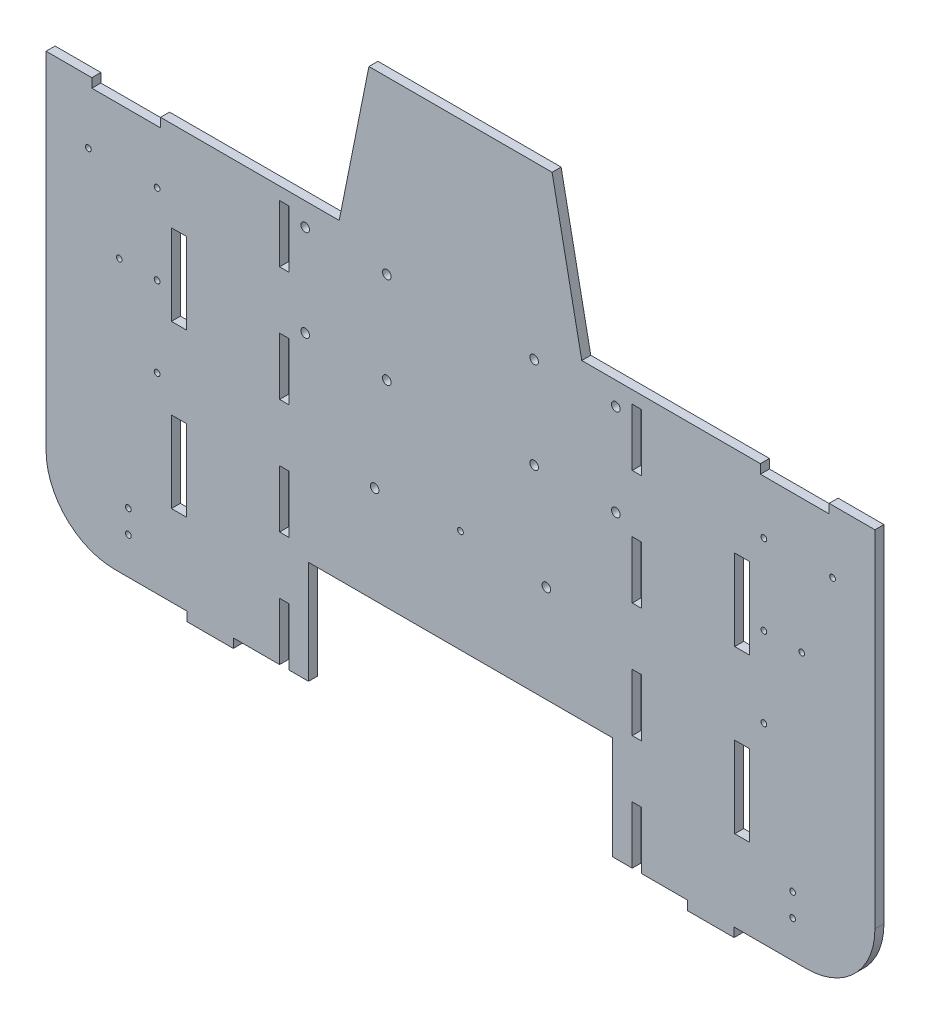
SolidWorks part; units mm, degrees
ref_plane "Front Plane" through (0, 0, 0) normal (0, 0, 1) x (1, 0, 0)
ref_plane "Top Plane" through (0, 0, 0) normal (0, 1, 0) x (1, 0, 0)
ref_plane "Right Plane" through (0, 0, 0) normal (1, 0, 0) x (0, 0, -1)
sketch "Sketch2" plane through (0, 0, 0) normal (0, 0, 1) x (1, 0, 0)
  line L0 (-408.9218, 152.7574) -> (-459.7218, 152.7574)
  line L1 (332.7218, 152.7574) -> (134.539, 152.7574)
  line L2 (-134.539, 152.7574) -> (-332.7218, 152.7574)
  line L3 (-101.6, 317.1426) -> (-134.539, 152.7574)
  line L4 (101.6, 317.1426) -> (-101.6, 317.1426)
  line L5 (-303.5218, -317.1426) -> (-303.5218, -306.9826)
  line L6 (-459.7218, 152.7574) -> (-459.7218, -230.7826)
  line L7 (459.7218, 152.7574) -> (408.9218, 152.7574)
  line L8 (-303.5218, -306.9826) -> (-383.5218, -306.9826)
  line L9 (-303.5218, -317.1426) -> (-252, -317.1426)
  line L10 (-168.529, -306.9826) -> (-190.5, -306.9826)
  line L11 (408.9218, 142.5974) -> (408.9218, 152.7574)
  line L12 (332.7218, 142.5974) -> (408.9218, 142.5974)
  line L13 (332.7218, 152.7574) -> (332.7218, 142.5974)
  line L14 (-408.9218, 142.5974) -> (-332.7218, 142.5974)
  line L15 (-408.9218, 152.7574) -> (-408.9218, 142.5974)
  line L16 (-332.7218, 142.5974) -> (-332.7218, 152.7574)
  line L17 (304.1585, -37.2346) -> (320.675, -37.2346)
  line L18 (304.1585, 52.6814) -> (304.1585, -37.2346)
  line L19 (320.675, 52.6814) -> (304.1585, 52.6814)
  line L20 (320.675, -37.2346) -> (320.675, 52.6814)
  line L21 (304.1585, -217.0666) -> (320.675, -217.0666)
  line L22 (320.675, -217.0666) -> (320.675, -127.1506)
  line L23 (320.675, -127.1506) -> (304.1585, -127.1506)
  line L24 (304.1585, -127.1506) -> (304.1585, -217.0666)
  line L25 (252, -306.9826) -> (200.66, -306.9826)
  line L26 (252, -317.1426) -> (252, -306.9826)
  line L27 (0, 317.1426) -> (0, 0) construction
  line L28 (0, 0) -> (0, -192.6826) construction
  line L30 (-320.675, -217.0666) -> (-304.1585, -217.0666)
  line L31 (-320.675, -127.1506) -> (-320.675, -217.0666)
  line L32 (-304.1585, -127.1506) -> (-320.675, -127.1506)
  line L33 (-304.1585, -217.0666) -> (-304.1585, -127.1506)
  line L34 (-304.1585, 52.6814) -> (-320.675, 52.6814)
  line L35 (-320.675, 52.6814) -> (-320.675, -37.2346)
  line L36 (-320.675, -37.2346) -> (-304.1585, -37.2346)
  line L37 (-304.1585, -37.2346) -> (-304.1585, 52.6814)
  line L38 (303.5218, -317.1426) -> (303.5218, -306.9826)
  line L39 (303.5218, -306.9826) -> (383.5218, -306.9826)
  line L40 (-252, -317.1426) -> (-252, -306.9826)
  line L41 (168.529, -306.9826) -> (168.529, -192.6826)
  line L42 (168.529, -192.6826) -> (-168.529, -192.6826)
  line L43 (-168.529, -192.6826) -> (-168.529, -306.9826)
  line L44 (-190.5, 75.1277) -> (-190.5, 11.4601) construction
  line L45 (-190.5, -52.225) -> (-190.5, -115.91) construction
  line L46 (-190.5, -179.5951) -> (-190.5, -243.2802) construction
  line L47 (190.5, 75.1277) -> (190.5, 14.3511) construction
  line L48 (190.5, -306.9826) -> (190.5, -243.2802)
  line L49 (190.5, 14.3511) -> (190.5, -115.91) construction
  line L50 (-190.5, -243.2802) -> (-190.5, -306.9826)
  line L51 (-200.66, -306.9826) -> (-252, -306.9826)
  line L52 (190.5, -115.91) -> (190.5, -243.2802) construction
  line L54 (190.5, -306.9826) -> (168.529, -306.9826)
  line L56 (459.7218, 152.7574) -> (459.7218, -230.7826)
  line L62 (101.6, 317.1426) -> (134.539, 152.7574)
  line L75 (200.66, -243.2802) -> (190.5, -243.2802)
  line L76 (200.66, -243.2802) -> (200.66, -306.9826)
  line L77 (-200.66, -243.2802) -> (-200.66, -306.9826)
  line L78 (-200.66, -243.2802) -> (-190.5, -243.2802)
  line L79 (200.66, -179.5951) -> (190.5, -179.5951)
  line L80 (190.5, -179.5951) -> (190.5, -115.91)
  line L81 (200.66, -115.91) -> (190.5, -115.91)
  line L82 (200.66, -115.91) -> (200.66, -179.5951)
  line L83 (190.5, -52.225) -> (190.5, 11.4601)
  line L84 (200.66, 11.4601) -> (190.5, 11.4601)
  line L85 (200.66, 11.4601) -> (200.66, -52.225)
  line L86 (200.66, -52.225) -> (190.5, -52.225)
  line L87 (200.66, 138.8128) -> (190.5, 138.8128)
  line L88 (190.5, 75.1277) -> (190.5, 138.8128)
  line L89 (200.66, 75.1277) -> (190.5, 75.1277)
  line L90 (200.66, 138.8128) -> (200.66, 75.1277)
  line L91 (-190.5, 75.1277) -> (-190.5, 138.8128)
  line L92 (-200.66, 138.8128) -> (-190.5, 138.8128)
  line L93 (-200.66, 138.8128) -> (-200.66, 75.1277)
  line L94 (-200.66, 75.1277) -> (-190.5, 75.1277)
  line L95 (-190.5, -52.225) -> (-190.5, 11.4601)
  line L96 (-200.66, 11.4601) -> (-190.5, 11.4601)
  line L97 (-200.66, 11.4601) -> (-200.66, -52.225)
  line L98 (-200.66, -52.225) -> (-190.5, -52.225)
  line L99 (-200.66, -115.91) -> (-200.66, -179.5951)
  line L100 (-200.66, -115.91) -> (-190.5, -115.91)
  line L101 (-190.5, -179.5951) -> (-190.5, -115.91)
  line L102 (-200.66, -179.5951) -> (-190.5, -179.5951)
  line L104 (252, -317.1426) -> (303.5218, -317.1426)
  arc A0 (-383.5218, -306.9826) -> (-459.7218, -230.7826) centre (-383.5218, -230.7826) cw
  arc A2 (383.5218, -306.9826) -> (459.7218, -230.7826) centre (383.5218, -230.7826) ccw
  circle A4 centre (368.427, -265.987) radius 3.175
  circle A5 centre (368.427, -240.587) radius 3.175
  circle A6 centre (336.5503, -94.6874) radius 3.175
  circle A7 centre (378.5738, -5.7874) radius 3.175
  circle A8 centre (336.5503, -5.7874) radius 3.175
  circle A9 centre (336.5503, 83.1126) radius 3.175
  circle A10 centre (412.7503, 83.1126) radius 3.175
  circle A11 centre (-412.7503, 83.1126) radius 3.175
  circle A12 centre (-336.5503, 83.1126) radius 3.175
  circle A13 centre (-336.5503, -5.7874) radius 3.175
  circle A14 centre (-378.5738, -5.7874) radius 3.175
  circle A15 centre (-336.5503, -94.6874) radius 3.175
  circle A16 centre (-368.427, -240.587) radius 3.175
  circle A17 centre (-368.427, -265.987) radius 3.175
  circle A18 centre (172.2755, 127.3574) radius 4.7625
  circle A19 centre (172.2755, 25.7574) radius 4.7625
  circle A20 centre (81.7245, 25.7574) radius 4.7625
  circle A21 centre (81.7245, 127.3574) radius 4.7625
  circle A22 centre (-81.7245, 25.7574) radius 4.7625
  circle A23 centre (-81.7245, 127.3574) radius 4.7625
  circle A24 centre (-172.2755, 127.3574) radius 4.7625
  circle A25 centre (-172.2755, 25.7574) radius 4.7625
  circle A26 centre (0, -78.3826) radius 3.175
  circle A27 centre (-95.25, -84.7326) radius 4.7625
  circle A28 centre (95.25, -84.7326) radius 4.7625
  dimension "D1" = 76.2
  dimension "D8" = 76.2
  dimension "D2" = 10.16
  dimension "D3" = 919.4436
  dimension "D4" = 139.0468
  dimension "D5" = 252
  dimension "D6" = 317.1426
  dimension "D7" = 152.7574
  dimension "D9" = 168.529
  dimension "D10" = 80
  dimension "D11" = 51.5218
  dimension "D12" = 10.16
  dimension "D13" = 190.5
  dimension "D14" = 190.5
  dimension "D15" = 50.8
  dimension "D17" = 50.8
  dimension "D18" = 76.2
extrude "Boss-Extrude1" add sketch "Sketch2" against normal blind 10
